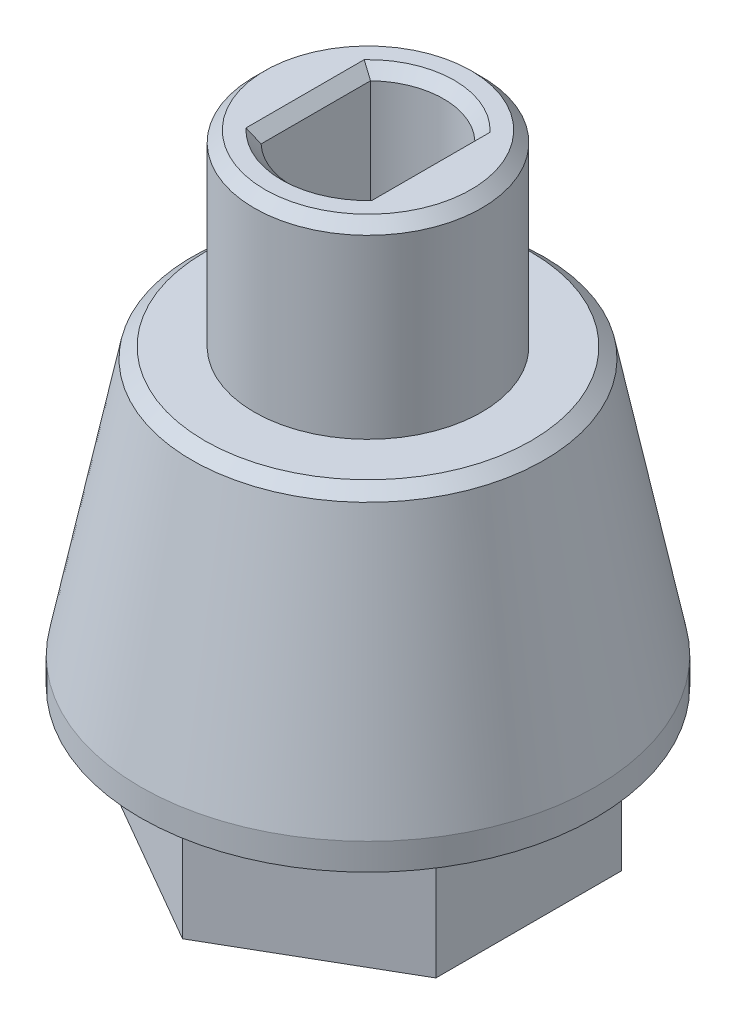
SolidWorks part; units mm, degrees
ref_plane "Front Plane" through (0, 0, 0) normal (0, 0, 1) x (1, 0, 0)
ref_plane "Top Plane" through (0, 0, 0) normal (0, 1, 0) x (1, 0, 0)
ref_plane "Right Plane" through (0, 0, 0) normal (1, 0, 0) x (0, 0, -1)
sketch "Sketch1" plane through (0, 0, 0) normal (0, 1, 0) x (1, 0, 0)
  line L0 (0, 6.9282) -> (0, -6.9282) construction
  line L1 (-6, -3.4641) -> (6, 3.4641) construction
  line L2 (6, -3.4641) -> (-6, 3.4641) construction
  line L3 (0, 6.9282) -> (6, 3.4641)
  line L4 (6, 3.4641) -> (6, -3.4641)
  line L5 (6, -3.4641) -> (0, -6.9282)
  line L6 (0, -6.9282) -> (-6, -3.4641)
  line L7 (-6, -3.4641) -> (-6, 3.4641)
  line L8 (-6, 3.4641) -> (0, 6.9282)
  dimension "D1" = 60
  dimension "D2" = 60
  dimension "D3" = 12
extrude "Boss-Extrude1" add sketch "Sketch1" along normal blind 4.7
sketch "Sketch2" plane through (0, 4.7, 0) normal (0, 1, 0) x (1, 0, 0)
  circle A0 centre (0, 0) radius 8.5
  dimension "D1" = 17
extrude "Boss-Extrude2" add sketch "Sketch2" along normal blind 1
sketch "Sketch3" plane through (0, 5.7, 0) normal (0, 1, 0) x (1, 0, 0)
  circle A0 centre (0, 0) radius 8.5
  circle A1 centre (0, 0) radius 8.5 construction
ref_plane "Plane1" through (0, 15.7, 0) normal (0, 1, 0) x (1, 0, 0)
sketch "Sketch4" plane through (0, 15.7, 0) normal (0, 1, 0) x (1, 0, 0)
  circle A0 centre (0, 0) radius 6.5
  dimension "D1" = 13
loft "Loft1" add profiles "Sketch4", "Sketch3"
sketch "Sketch5" plane through (0, 15.7, 0) normal (0, 1, 0) x (1, 0, 0)
  line L0 (-1.95, 2.044) -> (-1.95, -2.044)
  line L1 (1.95, 2.044) -> (1.95, -2.044)
  circle A0 centre (0, 0) radius 4.25
  arc A1 (-1.95, -2.044) -> (1.95, -2.044) centre (0, 0) ccw
  arc A2 (1.95, 2.044) -> (-1.95, 2.044) centre (0, 0) ccw
  dimension "D1" = 8.5
  dimension "D2" = 5.65
  dimension "D3" = 3.9
extrude "Boss-Extrude3" add sketch "Sketch5" along normal blind 7
chamfer "Chamfer1" distance 0.4 6 edges at (-1.95, 22.7, 0) (0, 22.7, -2.825) (1.95, 22.7, 0) (0, 22.7, 2.825) (0, 22.7, 4.25) (0, 15.7, 6.5)
sketch "Sketch6" plane through (0, 0, 0) normal (0, -1, 0) x (1, 0, 0)
  circle A0 centre (0, 0) radius 0.75
  dimension "D1" = 1.5
extrude "Cut-Extrude1" cut sketch "Sketch6" against normal blind 7
sketch "Sketch7" plane through (0, 15.7, 0) normal (0, 1, 0) x (1, 0, 0)
  line L8 (1.95, -2.044) -> (1.95, 2.044)
  line L9 (-1.95, 2.044) -> (-1.95, -2.044)
  line L10 (1.95, -2.044) -> (1.95, 2.044)
  line L11 (-1.95, 2.044) -> (-1.95, -2.044)
  arc A6 (1.95, 2.044) -> (-1.95, 2.044) centre (0, 0) ccw
  arc A7 (-1.95, -2.044) -> (1.95, -2.044) centre (0, 0) ccw
  arc A8 (1.95, 2.044) -> (-1.95, 2.044) centre (0, 0) ccw
  arc A9 (-1.95, -2.044) -> (1.95, -2.044) centre (0, 0) ccw
  dimension "D1" = 0
extrude "Cut-Extrude2" cut sketch "Sketch7" against normal blind 1
